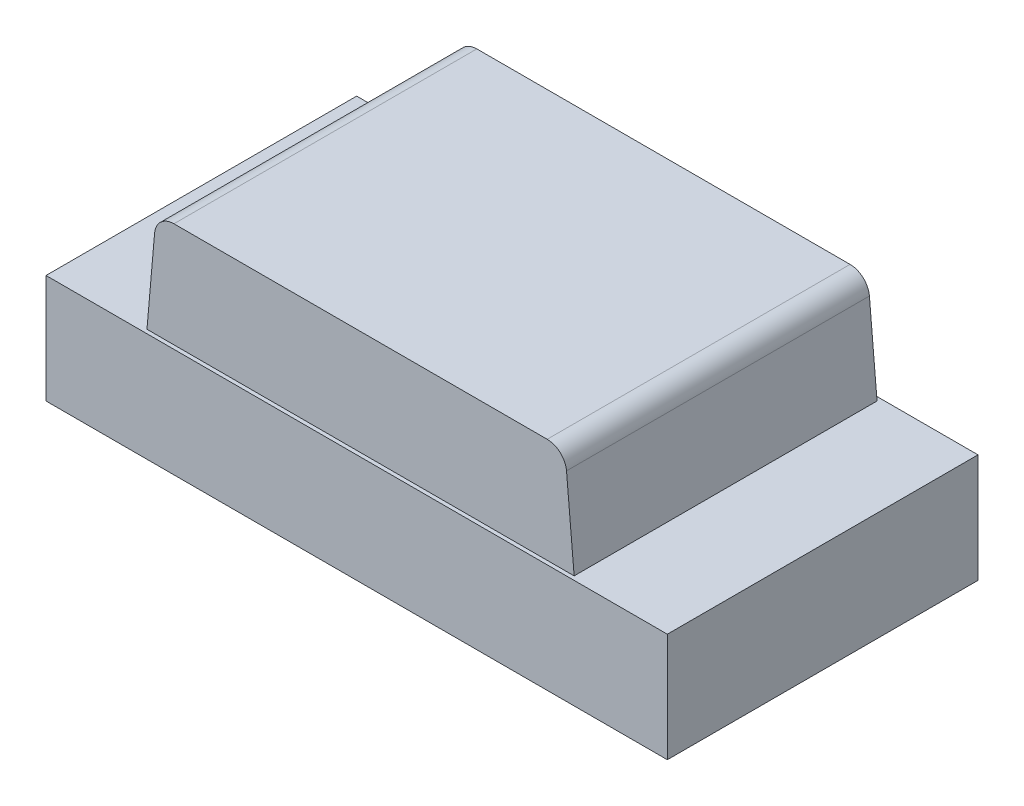
SolidWorks part; units mm, degrees
material "Alloy Steel"
ref_plane "Front Plane" through (0, 0, 0) normal (0, 0, 1) x (1, 0, 0)
ref_plane "Top Plane" through (0, 0, 0) normal (0, 1, 0) x (1, 0, 0)
ref_plane "Right Plane" through (0, 0, 0) normal (1, 0, 0) x (0, 0, -1)
sketch "Sketch1" plane through (0, 0, 0) normal (0, 1, 0) x (1, 0, 0)
  line L1 (0.8, -0.4) -> (-0.8, -0.4)
  line L2 (0.8, -0.4) -> (0.8, 0.4)
  line L3 (0.8, 0.4) -> (-0.8, 0.4)
  line L4 (-0.8, -0.4) -> (-0.8, 0.4)
  line L5 (0.8, -0.4) -> (-0.8, 0.4) construction
  line L6 (0.8, 0.4) -> (-0.8, -0.4) construction
  point P0 (0, 0)
  dimension "D1" = 0.8
  dimension "D2" = 1.6
extrude "Base" add sketch "Sketch1" along normal blind 0.28
sketch "Sketch2" plane through (0, 0, 0) normal (0, 0, 1) x (1, 0, 0)
  line L0 (-0.55, 0.28) -> (-0.5264, 0.55)
  line L1 (-0.8, 0.28) -> (0.8, 0.28) construction
  line L2 (-0.5264, 0.55) -> (0.5264, 0.55)
  line L3 (0.5264, 0.55) -> (0.55, 0.28)
  line L4 (0.55, 0.28) -> (-0.55, 0.28)
  line L5 (0.44, 0) -> (-0.44, 0) construction
  line L6 (0, -0.154) -> (0, 0.154) construction
  point P8 (0, 0.55)
  dimension "D1" = 1.1
  dimension "D2" = 0.55
  dimension "D3" = 10
extrude "Lens" add sketch "Sketch2" along normal offset from surface 0.01 and the other way offset from surface (0.39 mm away) 0.01 up to face at (0, 0.14, 0.4) other way up to face at (0, 0.14, -0.4)
fillet "Lens Rounds" radius 0.05 2 edges at (0.5264, 0.55, 0) (-0.5264, 0.55, 0)
